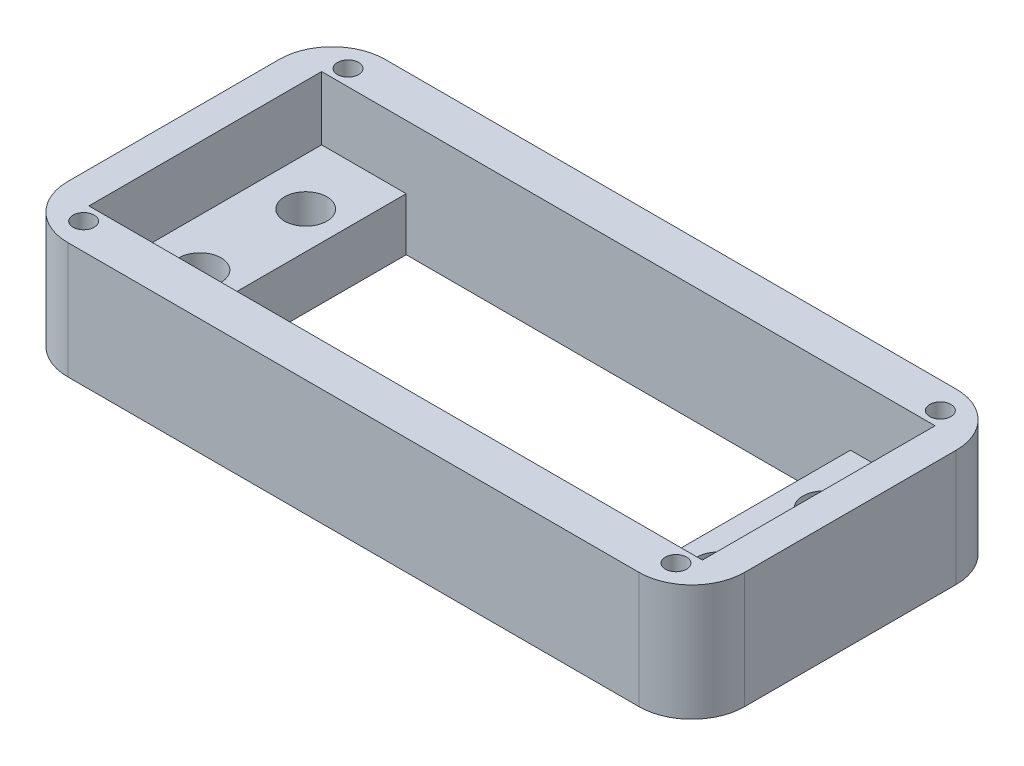
SolidWorks part; units mm, degrees
ref_plane "Front Plane" through (0, 0, 0) normal (0, 0, 1) x (1, 0, 0)
ref_plane "Top Plane" through (0, 0, 0) normal (0, 1, 0) x (1, 0, 0)
ref_plane "Right Plane" through (0, 0, 0) normal (1, 0, 0) x (0, 0, -1)
sketch "Sketch2" plane through (0, 0, 0) normal (0, 1, 0) x (1, 0, 0)
  line L1 (0, 0) -> (64, 0)
  line L2 (0, 0) -> (0, 30)
  line L3 (0, 30) -> (64, 30)
  line L4 (64, 0) -> (64, 30)
  dimension "D1" = 64
  dimension "D2" = 30
extrude "Boss-Extrude1" add sketch "Sketch2" along normal blind 64
sketch "Sketch3" plane through (0, 64, 0) normal (0, 1, 0) x (1, 0, 0)
  line L4 (0, 30) -> (0, 0) construction
  line L5 (11, 26) -> (53, 26)
  line L6 (11, 26) -> (11, 4)
  line L7 (11, 4) -> (53, 4)
  line L8 (53, 26) -> (53, 4)
  line L9 (64, 0) -> (64, 30) construction
  line L10 (0, 0) -> (64, 0) construction
  line L11 (64, 30) -> (0, 30) construction
  dimension "D1" = 11
  dimension "D2" = 11
  dimension "D3" = 4
  dimension "D4" = 4
extrude "Cut-Extrude1" cut sketch "Sketch3" against normal up to next
sketch "Sketch4" plane through (0, 64, 0) normal (0, 1, 0) x (1, 0, 0)
  line L0 (32, 30) -> (32, 0) construction
  line L1 (64, 30) -> (0, 30) construction
  line L2 (0, 0) -> (64, 0) construction
  line L3 (32, 15) -> (0, 15) construction
  line L4 (0, 30) -> (0, 0) construction
  line L5 (11, 26) -> (11, 4) construction
  circle A0 centre (7.5, 20) radius 2
  circle A2 centre (7.5, 10) radius 2
  circle A3 centre (56.5, 10) radius 2
  circle A4 centre (56.5, 20) radius 2
  dimension "D1" = 4
  dimension "D3" = 3.5
  dimension "D2" = 10
extrude "Cut-Extrude2" cut sketch "Sketch4" against normal up to next
sketch "Sketch5" plane through (0, 64, 0) normal (0, 1, 0) x (1, 0, 0)
  line L0 (3, 4) -> (61, 4)
  line L7 (3, 4) -> (3, 26)
  line L21 (3, 26) -> (61, 26)
  line L22 (61, 26) -> (61, 4)
  line L23 (53, 26) -> (11, 26) construction
  line L24 (0, 30) -> (0, 0) construction
  line L25 (64, 0) -> (64, 30) construction
  line L26 (64, 30) -> (0, 30) construction
  line L27 (0, 0) -> (64, 0) construction
  line L28 (64, 0) -> (64, 30)
  line L29 (64, 30) -> (0, 30)
  line L30 (0, 0) -> (64, 0)
  line L31 (0, 30) -> (0, 0)
  dimension "D1" = 3
  dimension "D2" = 3
extrude "Boss-Extrude2" add sketch "Sketch5" along normal blind 12
sketch "Sketch6" plane through (0, 76, 0) normal (0, 1, 0) x (1, 0, 0)
  line L0 (32, 30) -> (32, 0) construction
  line L1 (64, 30) -> (0, 30) construction
  line L2 (0, 0) -> (64, 0) construction
  line L3 (32, 15) -> (0, 15) construction
  line L4 (0, 30) -> (0, 0) construction
  circle A0 centre (4, 27.5) radius 1
  circle A1 centre (4, 2.5) radius 1
  circle A2 centre (60, 2.5) radius 1
  circle A3 centre (60, 27.5) radius 1
  dimension "D1" = 2
  dimension "D2" = 4
  dimension "D3" = 2.5
extrude "Cut-Extrude3" cut sketch "Sketch6" against normal up to next
fillet "Fillet1" radius 5 4 edges at (64, 38, -30) (64, 38, 0) (0, 38, -30) (0, 38, 0)
sketch "Sketch7" plane through (0, 0, 0) normal (0, -1, 0) x (1, 0, 0)
  line L4 (5, -30) -> (59, -30)
  line L5 (64, -25) -> (64, -5)
  line L6 (59, 0) -> (5, 0)
  line L7 (0, -5) -> (0, -25)
  line L8 (5, -30) -> (59, -30)
  line L9 (64, -25) -> (64, -5)
  line L10 (59, 0) -> (5, 0)
  line L11 (0, -5) -> (0, -25)
  arc A4 (59, -30) -> (64, -25) centre (59, -25) ccw
  arc A5 (64, -5) -> (59, 0) centre (59, -5) ccw
  arc A6 (5, 0) -> (0, -5) centre (5, -5) ccw
  arc A7 (0, -25) -> (5, -30) centre (5, -25) ccw
  arc A8 (59, -30) -> (64, -25) centre (59, -25) ccw
  arc A9 (64, -5) -> (59, 0) centre (59, -5) ccw
  arc A10 (5, 0) -> (0, -5) centre (5, -5) ccw
  arc A11 (0, -25) -> (5, -30) centre (5, -25) ccw
  dimension "D1" = 0
extrude "Cut-Extrude4" cut sketch "Sketch7" against normal offset from surface (59 mm away) 5 up to face at (7.5, 64, -12)
sketch "Sketch10" plane through (0, 76, 0) normal (0, 1, 0) x (1, 0, 0)
  line L4 (64, 5) -> (64, 25)
  line L5 (59, 30) -> (5, 30)
  line L6 (0, 25) -> (0, 5)
  line L7 (5, 0) -> (59, 0)
  line L8 (64, 5) -> (64, 25)
  line L9 (59, 30) -> (5, 30)
  line L10 (0, 25) -> (0, 5)
  line L11 (5, 0) -> (59, 0)
  arc A4 (64, 25) -> (59, 30) centre (59, 25) ccw
  arc A5 (5, 30) -> (0, 25) centre (5, 25) ccw
  arc A6 (0, 5) -> (5, 0) centre (5, 5) ccw
  arc A7 (59, 0) -> (64, 5) centre (59, 5) ccw
  arc A8 (64, 25) -> (59, 30) centre (59, 25) ccw
  arc A9 (5, 30) -> (0, 25) centre (5, 25) ccw
  arc A10 (0, 5) -> (5, 0) centre (5, 5) ccw
  arc A11 (59, 0) -> (64, 5) centre (59, 5) ccw
  dimension "D1" = 0
extrude "Cut-Extrude7" cut sketch "Sketch10" against normal blind 6
sketch "Sketch9" plane through (0, 76, 0) normal (0, 1, 0) x (1, 0, 0)
  line L4 (64, 5) -> (64, 25)
  line L5 (59, 30) -> (5, 30)
  line L6 (0, 25) -> (0, 5)
  line L7 (5, 0) -> (59, 0)
  line L8 (64, 5) -> (64, 25)
  line L9 (59, 30) -> (5, 30)
  line L10 (0, 25) -> (0, 5)
  line L11 (5, 0) -> (59, 0)
  arc A4 (64, 25) -> (59, 30) centre (59, 25) ccw
  arc A5 (5, 30) -> (0, 25) centre (5, 25) ccw
  arc A6 (0, 5) -> (5, 0) centre (5, 5) ccw
  arc A7 (59, 0) -> (64, 5) centre (59, 5) ccw
  arc A8 (64, 25) -> (59, 30) centre (59, 25) ccw
  arc A9 (5, 30) -> (0, 25) centre (5, 25) ccw
  arc A10 (0, 5) -> (5, 0) centre (5, 5) ccw
  arc A11 (59, 0) -> (64, 5) centre (59, 5) ccw
  dimension "D1" = 0
extrude "Cut-Extrude6" [suppressed] cut sketch "Sketch9" against normal up to surface (12 mm away)
